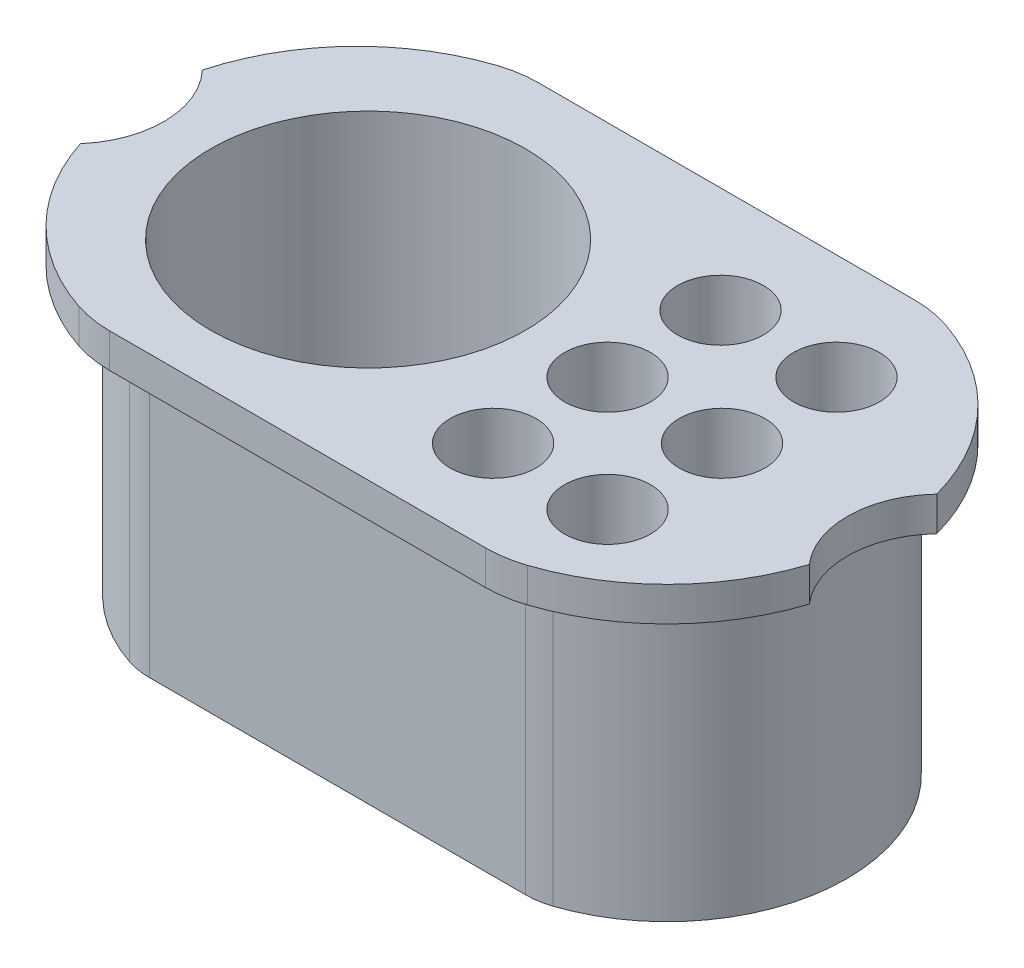
SolidWorks part; units mm, degrees
ref_plane "Front Plane" through (0, 0, 0) normal (0, 0, 1) x (1, 0, 0)
ref_plane "Top Plane" through (0, 0, 0) normal (0, 1, 0) x (1, 0, 0)
ref_plane "Right Plane" through (0, 0, 0) normal (1, 0, 0) x (0, 0, -1)
sketch "Sketch1" plane through (0, 0, 0) normal (0, 1, 0) x (1, 0, 0)
  line L4 (34.5405, 38.6091) -> (-36.4595, 38.6091)
  line L6 (34.5405, -36.3909) -> (-36.4595, -36.3909)
  arc A0 (-36.4595, 38.6091) -> (-36.4595, -36.3909) centre (-28.022, 1.1091) ccw
  arc A1 (34.5405, 38.6091) -> (34.5405, -36.3909) centre (26.103, 1.1091) cw
  point P11 (0.5405, 0.9091)
extrude "Boss-Extrude1" add sketch "Sketch1" along normal blind 6
fillet "Fillet1" radius 20 4 edges at (34.5405, 3, 36.3909) (34.5405, 3, -38.6091) (-36.4595, 3, -38.6091) (-36.4595, 3, 36.3909)
sketch "Sketch3" plane through (0, 0, 0) normal (0, -1, 0) x (1, 0, 0)
  line L4 (31.9074, 29.3909) -> (-33.8264, 29.3909)
  line L5 (-33.8264, -31.6091) -> (31.9074, -31.6091)
  line L6 (31.9074, 29.3909) -> (-33.8264, 29.3909)
  line L7 (-33.8264, -31.6091) -> (31.9074, -31.6091)
  arc A4 (36.0001, -30.9481) -> (36.0001, 28.7299) centre (26.103, -1.1091) ccw
  arc A5 (36.0001, -30.9481) -> (36.0001, 28.7299) centre (26.103, -1.1091) ccw
  arc A6 (-37.919, 28.7299) -> (-37.919, -30.9481) centre (-28.022, -1.1091) ccw
  arc A7 (-37.919, 28.7299) -> (-37.919, -30.9481) centre (-28.022, -1.1091) ccw
  arc A10 (-37.919, -30.9481) -> (-33.8264, -31.6091) centre (-33.8264, -18.6091) ccw
  arc A11 (-37.919, -30.9481) -> (-33.8264, -31.6091) centre (-33.8264, -18.6091) ccw
  arc A12 (36.0001, 28.7299) -> (31.9074, 29.3909) centre (31.9074, 16.3909) ccw
  arc A13 (36.0001, 28.7299) -> (31.9074, 29.3909) centre (31.9074, 16.3909) ccw
  arc A14 (31.9074, -31.6091) -> (36.0001, -30.9481) centre (31.9074, -18.6091) ccw
  arc A15 (-33.8264, 29.3909) -> (-37.919, 28.7299) centre (-33.8264, 16.3909) ccw
  arc A16 (31.9074, -31.6091) -> (36.0001, -30.9481) centre (31.9074, -18.6091) ccw
  arc A17 (-33.8264, 29.3909) -> (-37.919, 28.7299) centre (-33.8264, 16.3909) ccw
  dimension "D1" = 7
ref_plane "Plane1" through (31.9074, 0, -31.6091) normal (1, 0, 0) x (0, 0, -1)
sketch "Sketch4" plane through (31.9074, 0, -31.6091) normal (1, 0, 0) x (0, 0, -1)
  line L1 (0, 0) -> (-3, 0)
  line L2 (0, 0) -> (0, -50)
  line L3 (0, -50) -> (-3, -50)
  line L4 (-3, 0) -> (-3, -50)
sweep "Sweep1" add profiles "Sketch4" path "Sketch3"
sketch "Sketch6" plane through (0, 0, 0) normal (0, 1, 0) x (1, 0, 0)
  circle A0 centre (75, 0) radius 16.2457
  circle A1 centre (-76.919, 0) radius 16.2457
extrude "Cut-Extrude1" cut sketch "Sketch6" along normal blind 10
sketch "Sketch7" plane through (0, -50, 0) normal (0, -1, 0) x (1, 0, 0)
  line L11 (31.9074, 26.3909) -> (-33.8264, 26.3909)
  line L12 (-33.8264, -28.6091) -> (31.9074, -28.6091)
  line L13 (31.9074, 26.3909) -> (-33.8264, 26.3909)
  line L14 (-33.8264, -28.6091) -> (31.9074, -28.6091)
  arc A33 (35.0556, 25.8824) -> (31.9074, 26.3909) centre (31.9074, 16.3909) ccw
  arc A34 (-33.8264, 26.3909) -> (-36.9746, 25.8824) centre (-33.8264, 16.3909) ccw
  arc A35 (-36.9746, 25.8824) -> (-36.9746, -28.1007) centre (-28.022, -1.1091) ccw
  arc A36 (-36.9746, -28.1007) -> (-33.8264, -28.6091) centre (-33.8264, -18.6091) ccw
  arc A37 (31.9074, -28.6091) -> (35.0556, -28.1007) centre (31.9074, -18.6091) ccw
  arc A38 (35.0556, -28.1007) -> (35.0556, 25.8824) centre (26.103, -1.1091) ccw
  arc A39 (35.0556, 25.8824) -> (31.9074, 26.3909) centre (31.9074, 16.3909) ccw
  arc A40 (-33.8264, 26.3909) -> (-36.9746, 25.8824) centre (-33.8264, 16.3909) ccw
  arc A41 (-36.9746, 25.8824) -> (-36.9746, -28.1007) centre (-28.022, -1.1091) ccw
  arc A42 (-36.9746, -28.1007) -> (-33.8264, -28.6091) centre (-33.8264, -18.6091) ccw
  arc A43 (31.9074, -28.6091) -> (35.0556, -28.1007) centre (31.9074, -18.6091) ccw
  arc A44 (35.0556, -28.1007) -> (35.0556, 25.8824) centre (26.103, -1.1091) ccw
  dimension "D1" = 0
extrude "Boss-Extrude2" add sketch "Sketch7" against normal blind 3
sketch "Sketch9" plane through (0, 0, 0) normal (0, -1, 0) x (1, 0, 0)
  line L10 (-33.8264, -28.6091) -> (31.9074, -28.6091)
  line L11 (31.9074, 26.3909) -> (-33.8264, 26.3909)
  line L12 (-33.8264, -28.6091) -> (31.9074, -28.6091)
  line L13 (31.9074, 26.3909) -> (-33.8264, 26.3909)
  arc A34 (31.9074, -28.6091) -> (35.0556, -28.1007) centre (31.9074, -18.6091) ccw
  arc A35 (-36.9746, -28.1007) -> (-33.8264, -28.6091) centre (-33.8264, -18.6091) ccw
  arc A36 (-36.9746, 25.8824) -> (-36.9746, -28.1007) centre (-28.022, -1.1091) ccw
  arc A37 (-33.8264, 26.3909) -> (-36.9746, 25.8824) centre (-33.8264, 16.3909) ccw
  arc A38 (35.0556, 25.8824) -> (31.9074, 26.3909) centre (31.9074, 16.3909) ccw
  arc A39 (35.0556, -28.1007) -> (35.0556, 25.8824) centre (26.103, -1.1091) ccw
  arc A40 (31.9074, -28.6091) -> (35.0556, -28.1007) centre (31.9074, -18.6091) ccw
  arc A41 (-36.9746, -28.1007) -> (-33.8264, -28.6091) centre (-33.8264, -18.6091) ccw
  arc A42 (-36.9746, 25.8824) -> (-36.9746, -28.1007) centre (-28.022, -1.1091) ccw
  arc A43 (-33.8264, 26.3909) -> (-36.9746, 25.8824) centre (-33.8264, 16.3909) ccw
  arc A44 (35.0556, 25.8824) -> (31.9074, 26.3909) centre (31.9074, 16.3909) ccw
  arc A45 (35.0556, -28.1007) -> (35.0556, 25.8824) centre (26.103, -1.1091) ccw
  dimension "D1" = 3
extrude "Cut-Extrude2" cut sketch "Sketch9" against normal blind 44
sketch "Sketch10" plane through (0, -47, 0) normal (0, 1, 0) x (1, 0, 0)
  line L10 (31.9074, 28.6091) -> (-33.8264, 28.6091)
  line L11 (-33.8264, -26.3909) -> (31.9074, -26.3909)
  line L12 (31.9074, 28.6091) -> (-33.8264, 28.6091)
  line L13 (-33.8264, -26.3909) -> (31.9074, -26.3909)
  arc A35 (-33.8264, 28.6091) -> (-36.9746, 28.1007) centre (-33.8264, 18.6091) ccw
  arc A36 (35.0556, 28.1007) -> (31.9074, 28.6091) centre (31.9074, 18.6091) ccw
  arc A37 (35.0556, -25.8824) -> (35.0556, 28.1007) centre (26.103, 1.1091) ccw
  arc A38 (31.9074, -26.3909) -> (35.0556, -25.8824) centre (31.9074, -16.3909) ccw
  arc A39 (-36.9746, -25.8824) -> (-33.8264, -26.3909) centre (-33.8264, -16.3909) ccw
  arc A40 (-36.9746, 28.1007) -> (-36.9746, -25.8824) centre (-28.022, 1.1091) ccw
  arc A41 (-33.8264, 28.6091) -> (-36.9746, 28.1007) centre (-33.8264, 18.6091) ccw
  arc A42 (35.0556, 28.1007) -> (31.9074, 28.6091) centre (31.9074, 18.6091) ccw
  arc A43 (35.0556, -25.8824) -> (35.0556, 28.1007) centre (26.103, 1.1091) ccw
  arc A44 (31.9074, -26.3909) -> (35.0556, -25.8824) centre (31.9074, -16.3909) ccw
  arc A45 (-36.9746, -25.8824) -> (-33.8264, -26.3909) centre (-33.8264, -16.3909) ccw
  arc A46 (-36.9746, 28.1007) -> (-36.9746, -25.8824) centre (-28.022, 1.1091) ccw
  dimension "D1" = 0
extrude "Boss-Extrude3" add sketch "Sketch10" along normal up to surface (53 mm away) up to face at (-0.9595, 6, -1.1091)
sketch "Sketch11" plane through (0, 6, 0) normal (0, 1, 0) x (1, 0, 0)
  circle A0 centre (-25, 0) radius 27.5
  circle A2 centre (16.7482, 0.0933) radius 7.5
  circle A3 centre (16.7482, -19.9067) radius 7.5
  circle A4 centre (16.4863, 20.0916) radius 7.5
  circle A5 centre (36.7482, 0.0933) radius 7.5
  circle A6 centre (36.7482, -19.9067) radius 7.5
  circle A7 centre (36.7482, 20.0933) radius 7.5
  point P17 (0, 0)
extrude "Cut-Extrude4" cut sketch "Sketch11" against normal blind 50
